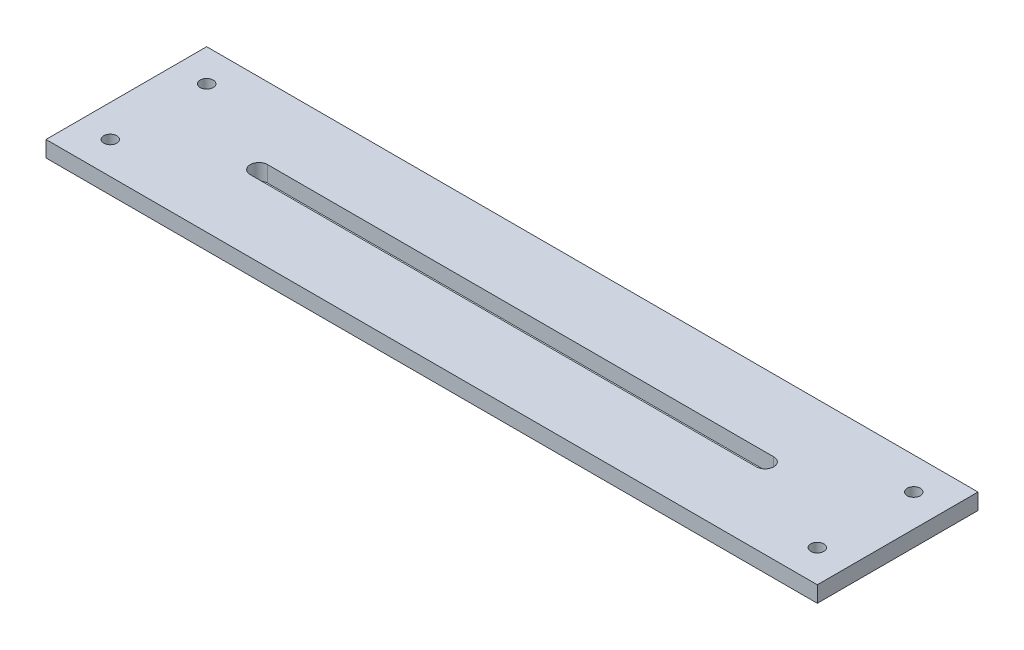
SolidWorks part; units mm, degrees
ref_plane "Front Plane" through (0, 0, 0) normal (0, 0, 1) x (1, 0, 0)
ref_plane "Top Plane" through (0, 0, 0) normal (0, 1, 0) x (1, 0, 0)
ref_plane "Right Plane" through (0, 0, 0) normal (1, 0, 0) x (0, 0, -1)
sketch "Sketch1" plane through (0, 0, 0) normal (0, 1, 0) x (1, 0, 0)
  line L0 (-100, 0) -> (100, 0) construction
  line L1 (152.4, 31.75) -> (-152.4, 31.75)
  line L2 (152.4, 31.75) -> (152.4, -31.75)
  line L3 (152.4, -31.75) -> (-152.4, -31.75)
  line L4 (-152.4, 31.75) -> (-152.4, -31.75)
  line L5 (152.4, 31.75) -> (-152.4, -31.75) construction
  line L6 (152.4, -31.75) -> (-152.4, 31.75) construction
  line L7 (-100, 3.429) -> (100, 3.429)
  line L8 (-100, -3.429) -> (100, -3.429)
  line L9 (0, 0) -> (0, 31.75) construction
  line L10 (-152.4, 0) -> (-103.429, 0) construction
  arc A0 (-100, 3.429) -> (-100, -3.429) centre (-100, 0) ccw
  arc A1 (100, -3.429) -> (100, 3.429) centre (100, 0) ccw
  circle A2 centre (-139.7, 19.05) radius 2.5797
  circle A3 centre (139.7, 19.05) radius 2.5797
  circle A4 centre (139.7, -19.05) radius 2.5797
  circle A5 centre (-139.7, -19.05) radius 2.5797
  point P0 (0, 0)
  point P8 (0, 0)
  dimension "D5" = 5.1594
  dimension "D1" = 304.8
  dimension "D2" = 63.5
  dimension "D3" = 200
  dimension "D4" = 6.858
  dimension "D6" = 12.7
  dimension "D7" = 12.7
extrude "Boss-Extrude1" add sketch "Sketch1" along normal blind 6.35
